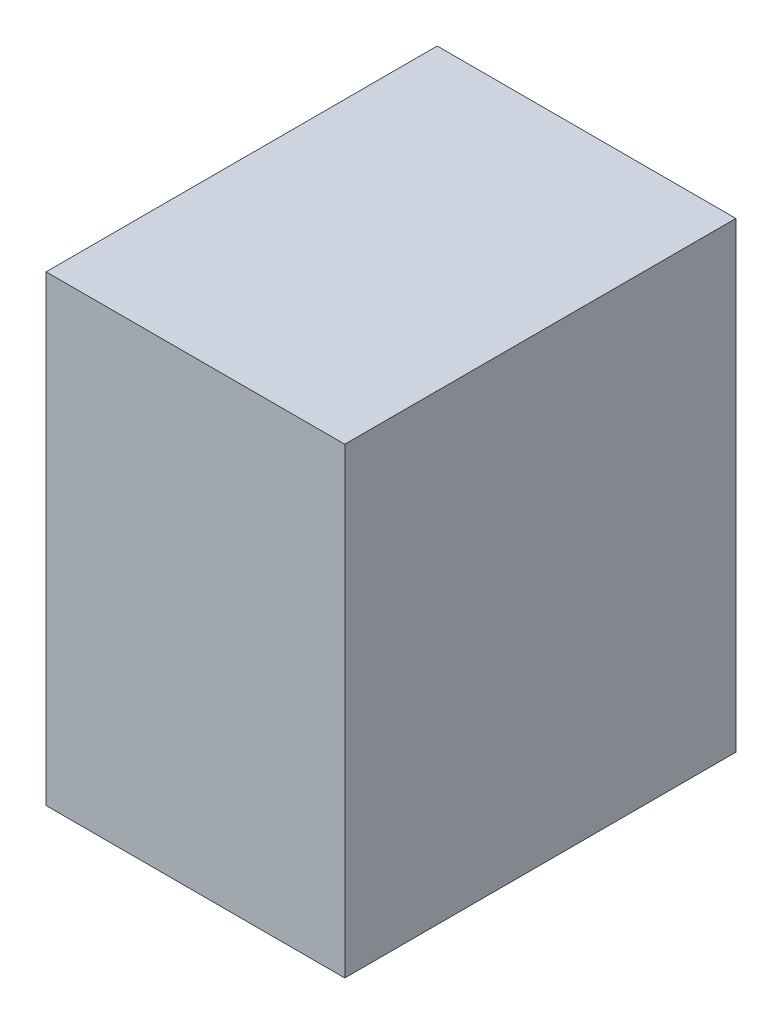
SolidWorks part; units mm, degrees
ref_plane "정면" through (0, 0, 0) normal (0, 0, 1) x (1, 0, 0)
ref_plane "윗면" through (0, 0, 0) normal (0, 1, 0) x (1, 0, 0)
ref_plane "우측면" through (0, 0, 0) normal (1, 0, 0) x (0, 0, -1)
sketch "스케치1" plane through (0, 0, 0) normal (0, 1, 0) x (1, 0, 0)
  line L1 (-21, -27.5) -> (21, -27.5)
  line L2 (-21, -27.5) -> (-21, 27.5)
  line L3 (-21, 27.5) -> (21, 27.5)
  line L4 (21, -27.5) -> (21, 27.5)
  line L5 (-21, -27.5) -> (21, 27.5) construction
  line L6 (-21, 27.5) -> (21, -27.5) construction
  point P0 (0, 0)
  dimension "D1" = 55
  dimension "D2" = 42
extrude "보스-돌출1" add sketch "스케치1" along normal blind 65
